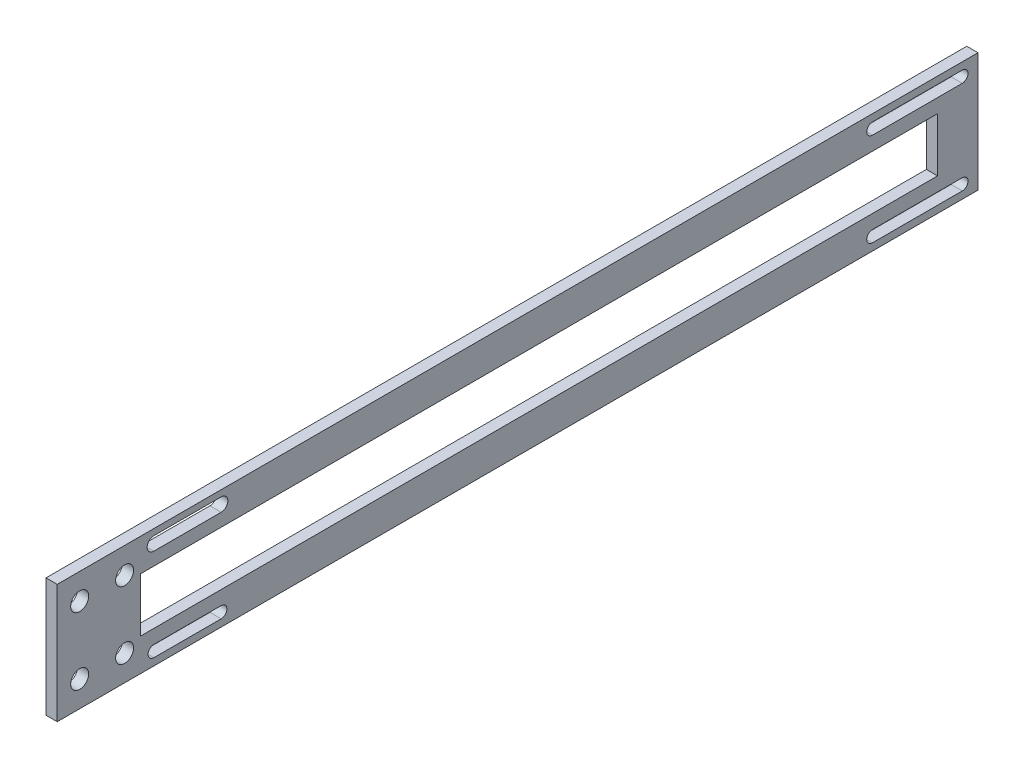
SolidWorks part; units mm, degrees
ref_plane "前视基准面" through (0, 0, 0) normal (0, 0, 1) x (1, 0, 0)
ref_plane "上视基准面" through (0, 0, 0) normal (0, 1, 0) x (1, 0, 0)
ref_plane "右视基准面" through (0, 0, 0) normal (1, 0, 0) x (0, 0, -1)
sketch "草图1" plane through (0, 0, 0) normal (0, 1, 0) x (1, 0, 0)
  line L1 (-3.2911, 395.443) -> (1.7089, 395.443)
  line L2 (-3.2911, 395.443) -> (-3.2911, -14.557)
  line L3 (-3.2911, -14.557) -> (1.7089, -14.557)
  line L4 (1.7089, 395.443) -> (1.7089, -14.557)
  dimension "D1" = 5
  dimension "D2" = 410
extrude "凸台-拉伸1" add sketch "草图1" along normal blind 53
sketch "草图2" plane through (1.7089, 0, 0) normal (1, 0, 0) x (0, 0, -1)
  line L0 (-14.557, 26.5) -> (58.443, 26.5) construction
  line L1 (-14.557, 53) -> (-14.557, 0) construction
  line L2 (58.443, 26.5) -> (58.443, 47.25) construction
  line L3 (58.443, 26.5) -> (58.443, 5.75) construction
  line L4 (58.443, 47.25) -> (28.443, 47.25) construction
  line L5 (58.443, 44.2805) -> (28.443, 44.2805)
  line L6 (58.443, 50.2195) -> (28.443, 50.2195)
  line L7 (58.443, 5.75) -> (28.443, 5.75) construction
  line L8 (58.443, 3.2) -> (28.443, 3.2)
  line L9 (58.443, 8.3) -> (28.443, 8.3)
  line L10 (58.443, 47.25) -> (348.443, 47.25) construction
  line L11 (348.443, 47.25) -> (348.443, 5.75) construction
  line L12 (348.443, 47.25) -> (388.443, 47.25) construction
  line L13 (348.443, 49.8) -> (388.443, 49.8)
  line L14 (348.443, 44.7) -> (388.443, 44.7)
  line L15 (348.443, 5.75) -> (388.443, 5.75) construction
  line L16 (348.443, 8.3) -> (388.443, 8.3)
  line L17 (348.443, 3.2) -> (388.443, 3.2)
  arc A0 (58.443, 44.2805) -> (58.443, 50.2195) centre (58.443, 47.25) ccw
  arc A1 (28.443, 50.2195) -> (28.443, 44.2805) centre (28.443, 47.25) ccw
  arc A2 (58.443, 3.2) -> (58.443, 8.3) centre (58.443, 5.75) ccw
  arc A3 (28.443, 8.3) -> (28.443, 3.2) centre (28.443, 5.75) ccw
  arc A4 (348.443, 49.8) -> (348.443, 44.7) centre (348.443, 47.25) ccw
  arc A5 (388.443, 44.7) -> (388.443, 49.8) centre (388.443, 47.25) ccw
  arc A6 (348.443, 8.3) -> (348.443, 3.2) centre (348.443, 5.75) ccw
  arc A7 (388.443, 3.2) -> (388.443, 8.3) centre (388.443, 5.75) ccw
  point P4 (43.443, 47.25)
  point P12 (43.443, 5.75)
  point P20 (368.443, 47.25)
  point P27 (368.443, 5.75)
  dimension "D5" = 2.9695
  dimension "D6" = 2.55
  dimension "D11" = 2.55
  dimension "D12" = 2.55
  dimension "D1" = 73
  dimension "D2" = 20.75
  dimension "D3" = 30
  dimension "D4" = 30
  dimension "D7" = 41.5
  dimension "D8" = 290
  dimension "D9" = 40
  dimension "D10" = 40
extrude "切除-拉伸1" cut sketch "草图2" against normal up to next
sketch "草图3" plane through (1.7089, 0, 0) normal (1, 0, 0) x (0, 0, -1)
  line L0 (-14.557, 26.5) -> (22.443, 26.5) construction
  line L1 (-14.557, 53) -> (-14.557, 0) construction
  line L2 (22.443, 26.5) -> (22.443, 38.5)
  line L3 (22.443, 26.5) -> (22.443, 14.5)
  line L4 (22.443, 38.5) -> (377.443, 38.5)
  line L5 (377.443, 38.5) -> (377.443, 14.5)
  line L6 (377.443, 14.5) -> (22.443, 14.5)
  dimension "D1" = 37
  dimension "D2" = 12
  dimension "D3" = 355
extrude "切除-拉伸2" cut sketch "草图3" against normal up to next
sketch "草图4" plane through (1.7089, 0, 0) normal (1, 0, 0) x (0, 0, -1)
  line L0 (-14.557, 26.5) -> (-4.557, 26.5) construction
  line L1 (-14.557, 53) -> (-14.557, 0) construction
  line L2 (-4.557, 26.5) -> (-4.557, 41.5) construction
  line L3 (-4.557, 26.5) -> (-4.557, 11.5) construction
  line L4 (-4.557, 26.5) -> (15.443, 26.5) construction
  line L5 (15.443, 26.5) -> (15.443, 41.5) construction
  line L6 (15.443, 26.5) -> (15.443, 11.5) construction
  circle A0 centre (-4.557, 41.5) radius 4
  circle A1 centre (15.443, 41.5) radius 4
  circle A2 centre (15.443, 11.5) radius 4
  circle A3 centre (-4.557, 11.5) radius 4
  dimension "D4" = 8
  dimension "D5" = 8
  dimension "D6" = 8
  dimension "D7" = 8
  dimension "D1" = 15
  dimension "D2" = 10
  dimension "D3" = 20
extrude "切除-拉伸3" cut sketch "草图4" against normal up to next
